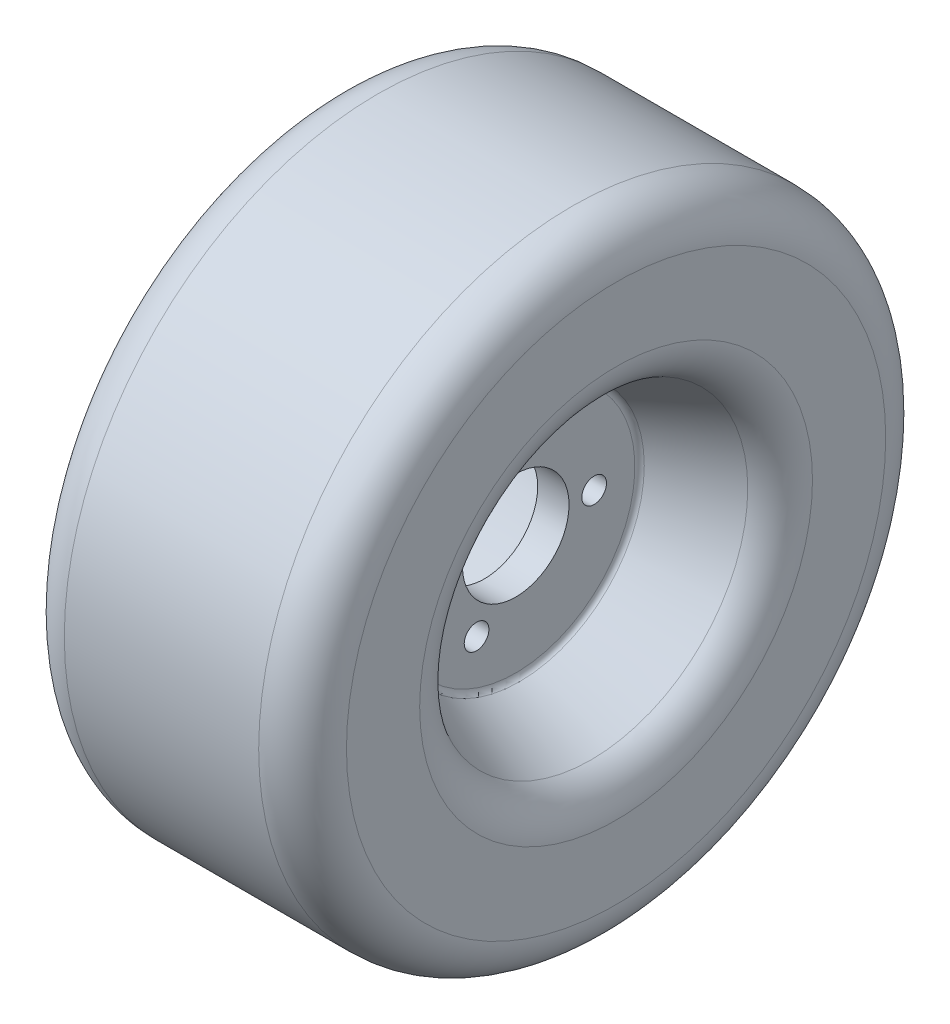
SolidWorks part; units mm, degrees
ref_plane "Front Plane" through (0, 0, 0) normal (0, 0, 1) x (1, 0, 0)
ref_plane "Top Plane" through (0, 0, 0) normal (0, 1, 0) x (1, 0, 0)
ref_plane "Right Plane" through (0, 0, 0) normal (1, 0, 0) x (0, 0, -1)
sketch "Sketch1" plane through (0, 0, 0) normal (0, 0, 1) x (1, 0, 0)
  line L0 (0, 0) -> (0, 127) construction
  line L2 (-39.37, 127) -> (39.37, 127)
  line L3 (-57.15, 109.22) -> (-57.15, 79.5644)
  line L5 (57.15, 109.22) -> (57.15, 79.5644)
  line L8 (-46.99, 63.5) -> (-46.99, 0) construction
  line L10 (46.99, 63.5) -> (46.99, 0) construction
  line L11 (46.99, 63.5) -> (16.51, 49.8917)
  line L14 (-46.99, 63.5) -> (3.7967, 49.8917)
  line L15 (3.7967, 49.8917) -> (3.7967, 0)
  line L16 (3.7967, 0) -> (16.51, 0)
  line L17 (16.51, 0) -> (16.51, 49.8917)
  arc A0 (46.99, 63.5) -> (57.15, 79.5644) centre (39.37, 79.5644) ccw
  arc A1 (39.37, 127) -> (57.15, 109.22) centre (39.37, 109.22) cw
  arc A2 (-57.15, 79.5644) -> (-46.99, 63.5) centre (-39.37, 79.5644) ccw
  arc A3 (-39.37, 127) -> (-57.15, 109.22) centre (-39.37, 109.22) ccw
  point P12 (57.15, 127)
  point P17 (-57.15, 127)
  dimension "D4" = 17.78
  dimension "D7" = 3.7967
  dimension "D1" = 114.3
  dimension "D2" = 127
  dimension "D3" = 93.98
  dimension "D5" = 16.51
  dimension "D6" = 63.5
  dimension "D8" = 105
sketch "Sketch3" plane through (0, 0, 0) normal (1, 0, 0) x (0, 0, -1)
  circle A0 centre (0, 0) radius 21.59
  dimension "D1" = 43.18
revolve "Revolve2" add sketch "Sketch1" angle 360 about L16
extrude "Cut-Extrude2" cut sketch "Sketch3" against normal through all both and the other way through all
sketch "Sketch4" plane through (0, 0, 0) normal (1, 0, 0) x (0, 0, -1)
  circle A0 centre (31.75, 0) radius 5
  circle A1 centre (-15.875, -27.4963) radius 5
  circle A2 centre (-15.875, 27.4963) radius 5
  point P9 (0, 0)
  dimension "D1" = 31.75
  dimension "D2" = 10
  dimension "D3" = 3
extrude "Cut-Extrude3" cut sketch "Sketch4" against normal through all both and the other way through all
fillet "Fillet1" radius 2.54 2 edges at (16.51, 0, 49.8917) (3.7967, 0, 49.8917)
